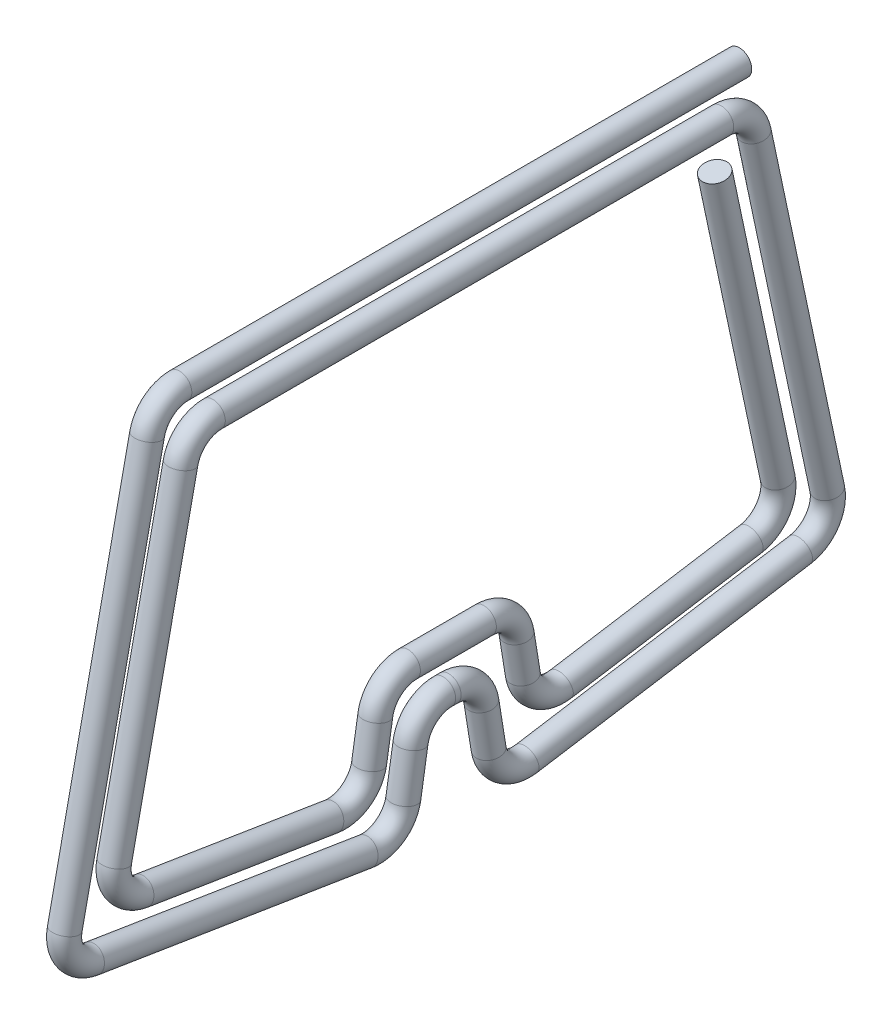
SolidWorks part; units mm, degrees
ref_plane "Спереди" through (0, 0, 0) normal (0, 0, 1) x (1, 0, 0)
ref_plane "Сверху" through (0, 0, 0) normal (0, 1, 0) x (1, 0, 0)
ref_plane "Справа" through (0, 0, 0) normal (1, 0, 0) x (0, 0, -1)
sketch "Эскиз1" plane through (0, 0, 0) normal (1, 0, 0) x (0, 0, -1)
  line L0 (0, 0) -> (0, -38) construction
  line L1 (-31.435, 0) -> (31.435, 0) construction
  line L2 (31.435, 0) -> (41, -45) construction
  line L3 (41, -45) -> (9.9312, -50) construction
  line L4 (9.9312, -50) -> (8, -38) construction
  line L5 (8, -38) -> (-8, -38) construction
  line L6 (-9.9312, -50) -> (-8, -38) construction
  line L7 (-41, -45) -> (-9.9312, -50) construction
  line L8 (-31.435, 0) -> (-41, -45) construction
  line L9 (46.9835, -49.1014) -> (5.7892, -55.7309) construction
  line L10 (5.7892, -55.7309) -> (3.7403, -43) construction
  line L11 (3.7403, -43) -> (-3.7403, -43) construction
  line L12 (-5.7892, -55.7309) -> (-3.7403, -43) construction
  line L13 (-46.9835, -49.1014) -> (-5.7892, -55.7309) construction
  line L14 (-35.4839, 5) -> (-46.9835, -49.1014) construction
  line L15 (-35.4839, 5) -> (35.4839, 5) construction
  line L16 (35.4839, 5) -> (46.9835, -49.1014) construction
  dimension "D1" = 50
  dimension "D2" = 38
  dimension "D3" = 8
  dimension "D4" = 102
  dimension "D5" = 45
  dimension "D6" = 41
  dimension "D7" = 5
sketch "Эскиз2" plane through (0, 0, 0) normal (1, 0, 0) x (0, 0, -1)
  line L0 (35.4839, 5) -> (-32.2447, 5)
  line L1 (-36.1573, 1.8316) -> (-46.1093, -44.9886)
  line L2 (-42.8323, -49.7695) -> (-9.7383, -55.0954)
  line L3 (-5.1536, -51.7817) -> (-4.2818, -46.3644)
  line L4 (-0.3326, -43) -> (0.3326, -43)
  line L5 (4.2818, -46.3644) -> (5.1536, -51.7817)
  line L6 (9.7383, -55.0954) -> (42.8323, -49.7695)
  line L7 (-35.4839, 5) -> (35.4839, 5) construction
  line L8 (31.435, 0) -> (41, -45) construction
  line L9 (46.9835, -49.1014) -> (5.7892, -55.7309) construction
  line L10 (46.1093, -44.9886) -> (37.2201, -3.1684)
  line L11 (33.3075, 0) -> (-28.1958, 0)
  line L12 (-32.1084, -3.1684) -> (-40.1258, -40.8872)
  line L13 (-36.8488, -45.6681) -> (-13.8804, -49.3644)
  line L14 (-9.2956, -46.0508) -> (-8.5415, -41.3644)
  line L15 (-4.5923, -38) -> (4.5923, -38)
  line L16 (8.5415, -41.3644) -> (9.2956, -46.0508)
  line L17 (13.8804, -49.3644) -> (36.8488, -45.6681)
  line L18 (41, -45) -> (9.9312, -50) construction
  line L19 (35.4839, 5) -> (46.9835, -49.1014) construction
  line L20 (40.1258, -40.8872) -> (32.4977, -5)
  arc A0 (-32.2447, 5) -> (-36.1573, 1.8316) centre (-32.2447, 1) ccw
  arc A1 (-46.1093, -44.9886) -> (-42.8323, -49.7695) centre (-42.1967, -45.8203) ccw
  arc A2 (-9.7383, -55.0954) -> (-5.1536, -51.7817) centre (-9.1028, -51.1462) ccw
  arc A3 (-4.2818, -46.3644) -> (-0.3326, -43) centre (-0.3326, -47) cw
  arc A4 (0.3326, -43) -> (4.2818, -46.3644) centre (0.3326, -47) cw
  arc A5 (5.1536, -51.7817) -> (9.7383, -55.0954) centre (9.1028, -51.1462) ccw
  arc A6 (42.8323, -49.7695) -> (46.1093, -44.9886) centre (42.1967, -45.8203) ccw
  arc A7 (-13.8804, -49.3644) -> (-9.2956, -46.0508) centre (-13.2448, -45.4153) ccw
  arc A8 (-8.5415, -41.3644) -> (-4.5923, -38) centre (-4.5923, -42) cw
  arc A9 (4.5923, -38) -> (8.5415, -41.3644) centre (4.5923, -42) cw
  arc A10 (9.2956, -46.0508) -> (13.8804, -49.3644) centre (13.2448, -45.4153) ccw
  arc A11 (40.1258, -40.8872) -> (36.8488, -45.6681) centre (36.2132, -41.7189) cw
  arc A12 (37.2201, -3.1684) -> (33.3075, 0) centre (33.3075, -4) ccw
  arc A13 (-28.1958, 0) -> (-32.1084, -3.1684) centre (-28.1958, -4) ccw
  arc A14 (-40.1258, -40.8872) -> (-36.8488, -45.6681) centre (-36.2132, -41.7189) ccw
  point P47 (-35.4839, 5)
  point P50 (-46.9835, -49.1014)
  point P53 (-5.7892, -55.7309)
  point P56 (-3.7403, -43)
  point P59 (3.7403, -43)
  point P62 (5.7892, -55.7309)
  point P65 (46.9835, -49.1014)
  point P68 (-9.9312, -50)
  point P71 (-8, -38)
  point P74 (8, -38)
  point P77 (9.9312, -50)
  point P80 (41, -45)
  point P83 (36.5467, 0)
  point P86 (-31.435, 0)
  point P89 (-41, -45)
  dimension "D2" = 4
  dimension "D1" = 5
ref_plane "Плоскость1" through (0, 5, -35.4839) normal (0, 0, -1) x (-1, 0, 0)
sketch "Эскиз3" plane through (0, 5, -35.4839) normal (0, 0, -1) x (-1, 0, 0)
  circle A0 centre (0, 0) radius 1.5
  dimension "D1" = 3
sweep "По траектории1" add profiles "Эскиз3" path "Эскиз2"
